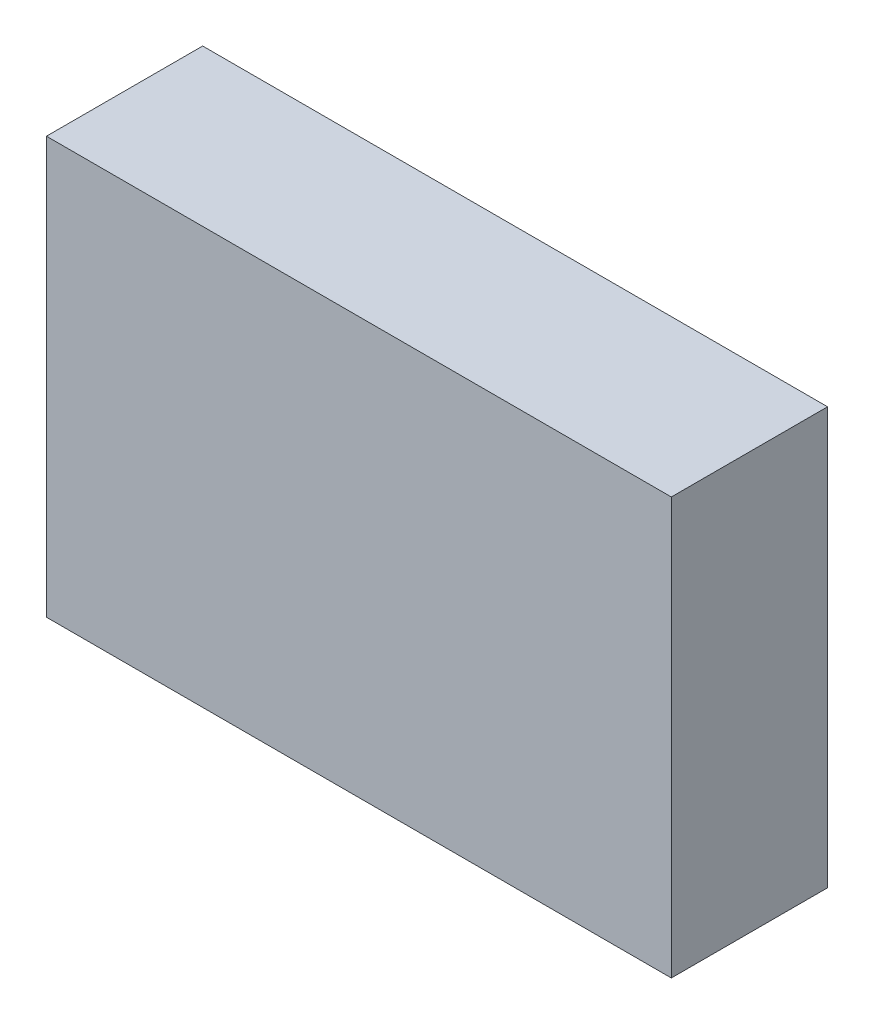
SolidWorks part; units mm, degrees
ref_plane "Front Plane" through (0, 0, 0) normal (0, 0, 1) x (1, 0, 0)
ref_plane "Top Plane" through (0, 0, 0) normal (0, 1, 0) x (1, 0, 0)
ref_plane "Right Plane" through (0, 0, 0) normal (1, 0, 0) x (0, 0, -1)
sketch "Sketch1" plane through (0, 0, 0) normal (0, 0, 1) x (1, 0, 0)
  line L1 (-30, -20) -> (30, -20)
  line L2 (-30, -20) -> (-30, 20)
  line L3 (-30, 20) -> (30, 20)
  line L4 (30, -20) -> (30, 20)
  line L5 (-30, -20) -> (30, 20) construction
  line L6 (-30, 20) -> (30, -20) construction
  point P0 (0, 0)
  dimension "D1" = 60
  dimension "D2" = 40
extrude "Boss-Extrude1" add sketch "Sketch1" along normal blind 15
